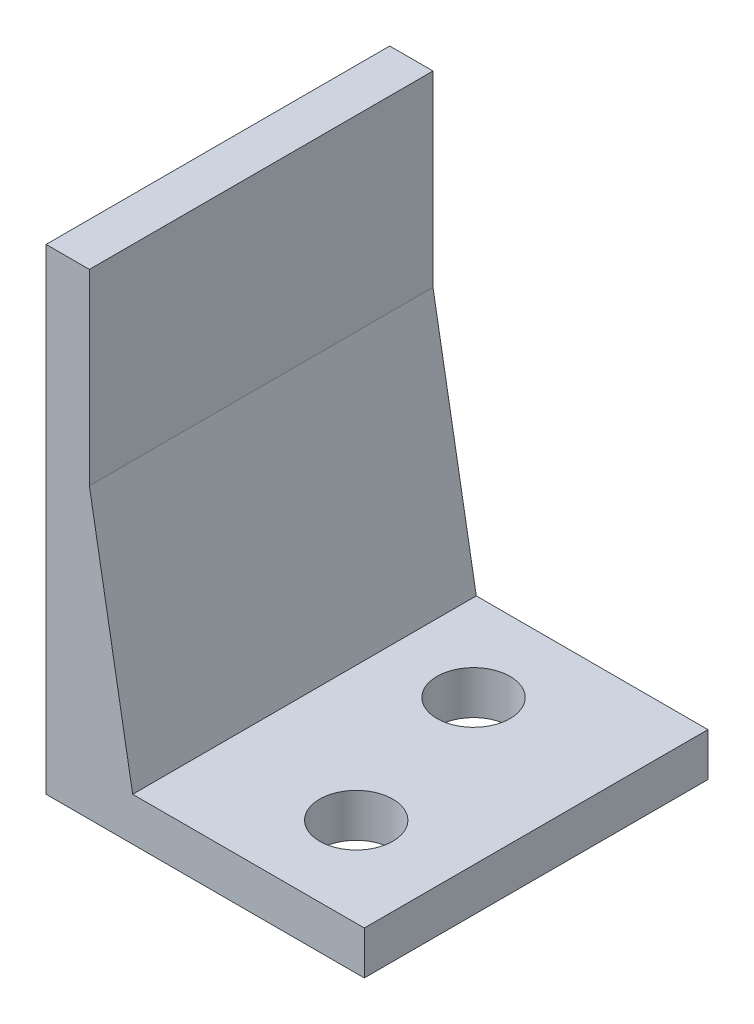
SolidWorks part; units mm, degrees
material "ABS"
ref_plane "Front Plane" through (0, 0, 0) normal (0, 0, 1) x (1, 0, 0)
ref_plane "Top Plane" through (0, 0, 0) normal (0, 1, 0) x (1, 0, 0)
ref_plane "Right Plane" through (0, 0, 0) normal (1, 0, 0) x (0, 0, -1)
sketch "Sketch1" plane through (0, 0, 0) normal (0, 0, 1) x (1, 0, 0)
  line L0 (0, 0) -> (0, 44)
  line L1 (0, 44) -> (4, 44)
  line L2 (4, 44) -> (4, 4)
  line L3 (4, 4) -> (29.4, 4)
  line L4 (29.4, 4) -> (29.4, 0)
  line L5 (29.4, 0) -> (0, 0)
  dimension "D1" = 4
  dimension "D2" = 25.4
  dimension "D3" = 40
extrude "Boss-Extrude1" add sketch "Sketch1" along normal blind 31.75
hole_wizard "1/4 Clearance Hole1" positions "Sketch2" profile "Sketch3" hole size "1/4" standard "ANSI Inch" end condition through all
sketch "Sketch2" plane through (0, 4, 0) normal (0, 1, 0) x (1, 0, 0)
  line L0 (4, -31.75) -> (4, 0) construction
  line L1 (29.4, -31.75) -> (29.4, 0) construction
  point P0 (20.4, -23.495)
  point P2 (16, -8.255)
  point P10 (29.4, -15.875)
  dimension "D1" = 16.4
  dimension "D2" = 12
  dimension "D3" = 15.24
  dimension "D4" = 7.62
sketch "Sketch3" plane through (20.4, 4, 23.495) normal (1, 0, 0) x (0, 0, 1)
  line L0 (0, 0) -> (0, 4)
  line L1 (0, 4) -> (3.3782, 4)
  line L2 (3.3782, 4) -> (3.3782, 0)
  line L5 (3.3782, 0) -> (0, 0)
  line L11 (0, -6.35) -> (0, 107.95) construction
  dimension "Thru Hole Dia." = 6.7564
  dimension "Thru Hole Depth" = 4
chamfer "Chamfer1" distance 4 angle 80 1 edges at (4, 4, 15.875)
equation "\"D4@Sketch2\"=\"D3@Sketch2\"/2"
